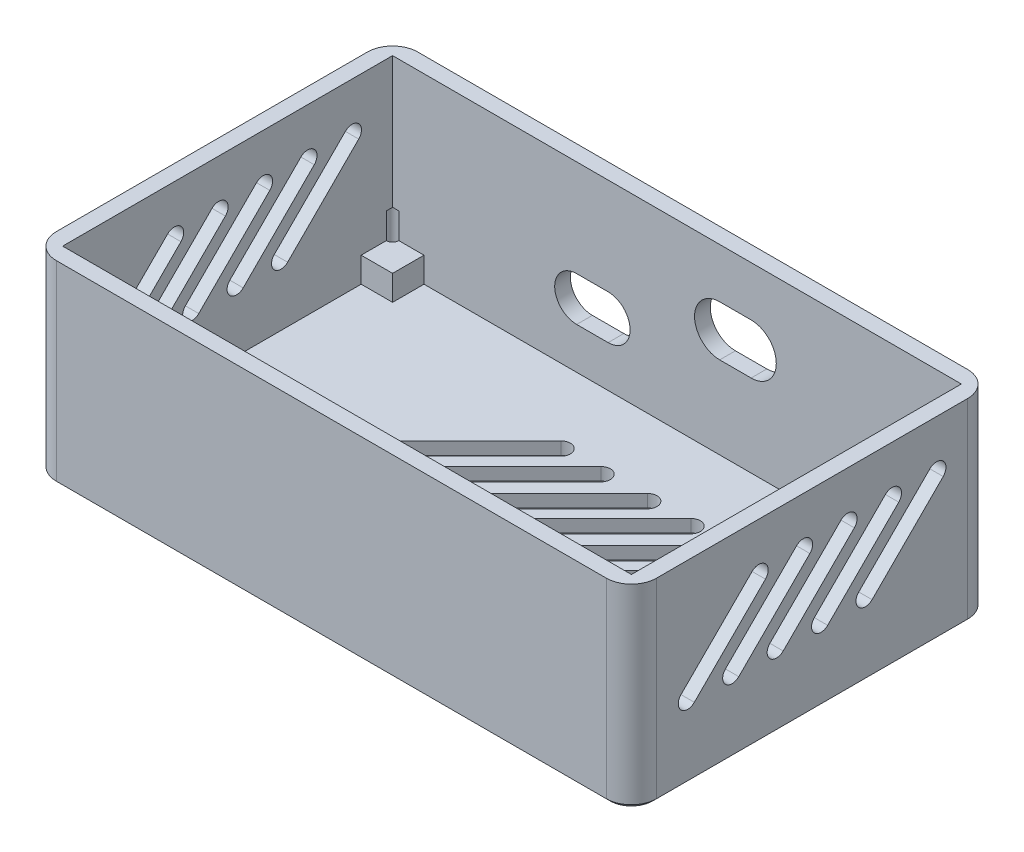
SolidWorks part; units mm, degrees
ref_plane "Front Plane" through (0, 0, 0) normal (0, 0, 1) x (1, 0, 0)
ref_plane "Top Plane" through (0, 0, 0) normal (0, 1, 0) x (1, 0, 0)
ref_plane "Right Plane" through (0, 0, 0) normal (1, 0, 0) x (0, 0, -1)
sketch "Croquis_contorno" plane through (0, 0, 0) normal (0, 1, 0) x (1, 0, 0)
  line L0 (-43.75, -28.75) -> (43.75, -28.75)
  line L1 (47.75, -24.75) -> (47.75, 24.75)
  line L2 (43.75, 28.75) -> (-43.75, 28.75)
  line L3 (-47.75, 24.75) -> (-47.75, -24.75)
  arc A0 (43.75, -28.75) -> (47.75, -24.75) centre (43.75, -24.75) ccw
  arc A1 (47.75, 24.75) -> (43.75, 28.75) centre (43.75, 24.75) ccw
  arc A2 (-43.75, 28.75) -> (-47.75, 24.75) centre (-43.75, 24.75) ccw
  arc A3 (-47.75, -24.75) -> (-43.75, -28.75) centre (-43.75, -24.75) ccw
  dimension "D3" = 4
  dimension "D1" = 95.5
  dimension "D2" = 57.5
extrude "Cuerpo" add sketch "Croquis_contorno" along normal blind 31
ref_plane "Plano_Top Plane_+31" through (0, 31, 0) normal (0, 1, 0) x (1, 0, 0)
sketch "Croquis_hueco_PCB" plane through (0, 31, 0) normal (0, 1, 0) x (1, 0, 0)
  line L1 (-45.25, -26.25) -> (45.25, -26.25)
  line L2 (-45.25, -26.25) -> (-45.25, 26.25)
  line L3 (-45.25, 26.25) -> (45.25, 26.25)
  line L4 (45.25, -26.25) -> (45.25, 26.25)
  line L5 (-45.25, -26.25) -> (45.25, 26.25) construction
  line L6 (-45.25, 26.25) -> (45.25, -26.25) construction
  dimension "D1" = 90.5
  dimension "D2" = 52.5
extrude "Hueco_PCB" cut sketch "Croquis_hueco_PCB" against normal blind 29
ref_plane "Plano_Top Plane_+2" through (0, 2, 0) normal (0, 1, 0) x (1, 0, 0)
sketch "Croquis_apoyos" plane through (0, 2, 0) normal (0, 1, 0) x (1, 0, 0)
  line L0 (45.25, 26.25) -> (-45.25, 26.25) construction
  line L1 (-45.25, -26.25) -> (-40.25, -26.25)
  line L2 (-45.25, -26.25) -> (-45.25, -21.25)
  line L3 (-45.25, -21.25) -> (-40.25, -21.25)
  line L4 (-40.25, -26.25) -> (-40.25, -21.25)
  line L5 (-45.25, -26.25) -> (-40.25, -21.25) construction
  line L6 (-45.25, -21.25) -> (-40.25, -26.25) construction
  line L7 (-45.25, 21.25) -> (-40.25, 21.25)
  line L8 (-45.25, 21.25) -> (-45.25, 26.25)
  line L9 (-45.25, 26.25) -> (-40.25, 26.25)
  line L10 (-40.25, 21.25) -> (-40.25, 26.25)
  line L11 (-45.25, 21.25) -> (-40.25, 26.25) construction
  line L12 (-45.25, 26.25) -> (-40.25, 21.25) construction
  line L13 (45.25, -26.25) -> (45.25, 26.25) construction
  line L14 (40.25, -26.25) -> (45.25, -26.25)
  line L15 (40.25, -26.25) -> (40.25, -21.25)
  line L16 (40.25, -21.25) -> (45.25, -21.25)
  line L17 (45.25, -26.25) -> (45.25, -21.25)
  line L18 (40.25, -26.25) -> (45.25, -21.25) construction
  line L19 (40.25, -21.25) -> (45.25, -26.25) construction
  line L21 (40.25, 21.25) -> (45.25, 21.25)
  line L22 (40.25, 21.25) -> (40.25, 26.25)
  line L23 (40.25, 26.25) -> (45.25, 26.25)
  line L24 (45.25, 21.25) -> (45.25, 26.25)
  line L25 (40.25, 21.25) -> (45.25, 26.25) construction
  line L26 (40.25, 26.25) -> (45.25, 21.25) construction
  point P0 (-42.75, 23.75)
  point P11 (42.75, -23.75)
  point P18 (42.75, 23.75)
  dimension "D1" = 5
  dimension "D2" = 5
extrude "Apoyos_PCB" add sketch "Croquis_apoyos" along normal blind 4
sketch "Croquis_alivios" plane through (0, 2, 0) normal (0, 1, 0) x (1, 0, 0)
  circle A0 centre (-45.25, -26.25) radius 1
  circle A1 centre (-45.25, 26.25) radius 1
  circle A2 centre (45.25, -26.25) radius 1
  circle A3 centre (45.25, 26.25) radius 1
  dimension "D1" = 2
extrude "Alivios_esquinas" cut sketch "Croquis_alivios" along normal blind 8.1
sketch "Croquis_salidas" plane through (0, 0, 0) normal (0, 0, 1) x (1, 0, 0)
  line L0 (6.8, 19.1) -> (11.8, 19.1) construction
  line L1 (6.8, 23.1) -> (11.8, 23.1)
  line L2 (6.8, 15.1) -> (11.8, 15.1)
  line L3 (-15.96, 12.1) -> (-10.96, 12.1) construction
  line L4 (-15.96, 15.6) -> (-10.96, 15.6)
  line L5 (-15.96, 8.6) -> (-10.96, 8.6)
  arc A0 (6.8, 23.1) -> (6.8, 15.1) centre (6.8, 19.1) ccw
  arc A1 (11.8, 15.1) -> (11.8, 23.1) centre (11.8, 19.1) ccw
  arc A2 (-15.96, 15.6) -> (-15.96, 8.6) centre (-15.96, 12.1) ccw
  arc A3 (-10.96, 8.6) -> (-10.96, 15.6) centre (-10.96, 12.1) ccw
  point P2 (9.3, 19.1)
  point P7 (-13.46, 12.1)
  point P14 (0, 0)
extrude "Salidas_USB_y_panel" cut sketch "Croquis_salidas" against normal through all
sketch "Croquis_ventilas" plane through (0, 0, 0) normal (1, 0, 0) x (0, 0, -1)
  line L0 (-19.799, 11.9431) -> (-8.4853, 23.2569) construction
  line L1 (-20.8597, 13.0038) -> (-9.5459, 24.3175)
  line L2 (-18.7383, 10.8825) -> (-7.4246, 22.1962)
  line L3 (-12.7279, 11.9431) -> (-1.4142, 23.2569) construction
  line L4 (-13.7886, 13.0038) -> (-2.4749, 24.3175)
  line L5 (-11.6673, 10.8825) -> (-0.3536, 22.1962)
  line L6 (-5.6569, 11.9431) -> (5.6569, 23.2569) construction
  line L7 (-6.7175, 13.0038) -> (4.5962, 24.3175)
  line L8 (-4.5962, 10.8825) -> (6.7175, 22.1962)
  line L9 (1.4142, 11.9431) -> (12.7279, 23.2569) construction
  line L10 (0.3536, 13.0038) -> (11.6673, 24.3175)
  line L11 (2.4749, 10.8825) -> (13.7886, 22.1962)
  line L12 (8.4853, 11.9431) -> (19.799, 23.2569) construction
  line L13 (7.4246, 13.0038) -> (18.7383, 24.3175)
  line L14 (9.5459, 10.8825) -> (20.8597, 22.1962)
  arc A0 (-20.8597, 13.0038) -> (-18.7383, 10.8825) centre (-19.799, 11.9431) ccw
  arc A1 (-7.4246, 22.1962) -> (-9.5459, 24.3175) centre (-8.4853, 23.2569) ccw
  arc A2 (-13.7886, 13.0038) -> (-11.6673, 10.8825) centre (-12.7279, 11.9431) ccw
  arc A3 (-0.3536, 22.1962) -> (-2.4749, 24.3175) centre (-1.4142, 23.2569) ccw
  arc A4 (-6.7175, 13.0038) -> (-4.5962, 10.8825) centre (-5.6569, 11.9431) ccw
  arc A5 (6.7175, 22.1962) -> (4.5962, 24.3175) centre (5.6569, 23.2569) ccw
  arc A6 (0.3536, 13.0038) -> (2.4749, 10.8825) centre (1.4142, 11.9431) ccw
  arc A7 (13.7886, 22.1962) -> (11.6673, 24.3175) centre (12.7279, 23.2569) ccw
  arc A8 (7.4246, 13.0038) -> (9.5459, 10.8825) centre (8.4853, 11.9431) ccw
  arc A9 (20.8597, 22.1962) -> (18.7383, 24.3175) centre (19.799, 23.2569) ccw
  point P2 (-14.1421, 17.6)
  point P7 (-7.0711, 17.6)
  point P14 (0, 17.6)
  point P21 (7.0711, 17.6)
  point P28 (14.1421, 17.6)
  point P35 (0, 0)
extrude "Ventilas_laterales" cut sketch "Croquis_ventilas" along normal through all and the other way through all
sketch "Croquis_rejilla_piso" plane through (0, 0, 0) normal (0, 1, 0) x (1, 0, 0)
  line L0 (-35.7089, -14.4957) -> (-6.7175, 14.4957) construction
  line L1 (-36.7696, -13.435) -> (-7.7782, 15.5563)
  line L2 (-34.6482, -15.5563) -> (-5.6569, 13.435)
  line L3 (-28.6378, -14.4957) -> (0, 14.1421) construction
  line L4 (-29.6985, -13.435) -> (-1.0607, 15.2028)
  line L5 (-27.5772, -15.5563) -> (1.0607, 13.0815)
  line L6 (-21.2132, -14.4957) -> (7.4246, 14.1421) construction
  line L7 (-22.2739, -13.435) -> (6.364, 15.2028)
  line L8 (-20.1525, -15.5563) -> (8.4853, 13.0815)
  line L9 (-14.3189, -14.4957) -> (14.3189, 14.1421) construction
  line L10 (-15.3796, -13.435) -> (13.2583, 15.2028)
  line L11 (-13.2583, -15.5563) -> (15.3796, 13.0815)
  line L12 (-6.8943, -14.4957) -> (21.7435, 14.1421) construction
  line L13 (-7.955, -13.435) -> (20.6829, 15.2028)
  line L14 (-5.8336, -15.5563) -> (22.8042, 13.0815)
  line L15 (0, -14.4957) -> (28.6378, 14.1421) construction
  line L16 (-1.0607, -13.435) -> (27.5772, 15.2028)
  line L17 (1.0607, -15.5563) -> (29.6985, 13.0815)
  line L18 (6.364, -14.4957) -> (35.5321, 14.6725) construction
  line L19 (5.3033, -13.435) -> (34.4715, 15.7331)
  line L20 (7.4246, -15.5563) -> (36.5928, 13.6118)
  arc A0 (-36.7696, -13.435) -> (-34.6482, -15.5563) centre (-35.7089, -14.4957) ccw
  arc A1 (-5.6569, 13.435) -> (-7.7782, 15.5563) centre (-6.7175, 14.4957) ccw
  arc A2 (-29.6985, -13.435) -> (-27.5772, -15.5563) centre (-28.6378, -14.4957) ccw
  arc A3 (1.0607, 13.0815) -> (-1.0607, 15.2028) centre (0, 14.1421) ccw
  arc A4 (-22.2739, -13.435) -> (-20.1525, -15.5563) centre (-21.2132, -14.4957) ccw
  arc A5 (8.4853, 13.0815) -> (6.364, 15.2028) centre (7.4246, 14.1421) ccw
  arc A6 (-15.3796, -13.435) -> (-13.2583, -15.5563) centre (-14.3189, -14.4957) ccw
  arc A7 (15.3796, 13.0815) -> (13.2583, 15.2028) centre (14.3189, 14.1421) ccw
  arc A8 (-7.955, -13.435) -> (-5.8336, -15.5563) centre (-6.8943, -14.4957) ccw
  arc A9 (22.8042, 13.0815) -> (20.6829, 15.2028) centre (21.7435, 14.1421) ccw
  arc A10 (-1.0607, -13.435) -> (1.0607, -15.5563) centre (0, -14.4957) ccw
  arc A11 (29.6985, 13.0815) -> (27.5772, 15.2028) centre (28.6378, 14.1421) ccw
  arc A12 (5.3033, -13.435) -> (7.4246, -15.5563) centre (6.364, -14.4957) ccw
  arc A13 (36.5928, 13.6118) -> (34.4715, 15.7331) centre (35.5321, 14.6725) ccw
  point P2 (-21.2132, 0)
  point P7 (-14.3189, -0.1768)
  point P14 (-6.8943, -0.1768)
  point P21 (0, -0.1768)
  point P28 (7.4246, -0.1768)
  point P35 (14.3189, -0.1768)
  point P42 (20.948, 0.0884)
  point P49 (0, 0)
extrude "Rejilla_piso" cut sketch "Croquis_rejilla_piso" along normal blind 2
chamfer "Chaflan_base" distance 0.6 angle 45 8 edges at (0, 0, 28.75) (46.5784, 0, 27.5784) (47.75, 0, 0) (46.5784, 0, -27.5784) (0, 0, -28.75) (-46.5784, 0, -27.5784) (-47.75, 0, 0) (-46.5784, 0, 27.5784)
